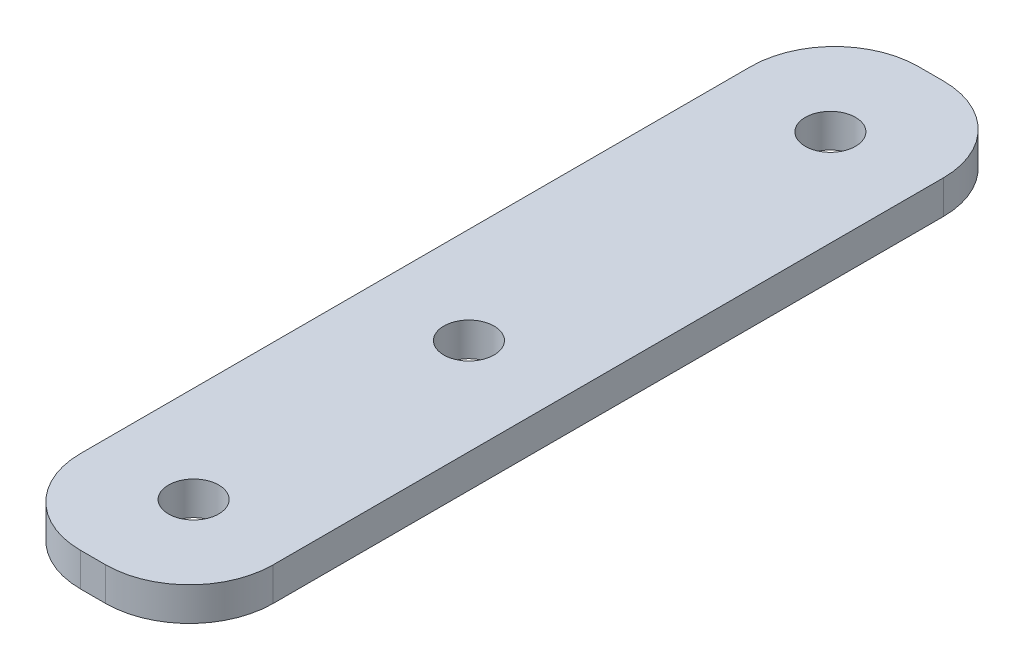
SolidWorks part; units mm, degrees
material "3.0205 (EN-AW 1200)"
ref_plane "Plan de face" through (0, 0, 0) normal (0, 0, 1) x (1, 0, 0)
ref_plane "Plan de dessus" through (0, 0, 0) normal (0, 1, 0) x (1, 0, 0)
ref_plane "Plan de droite" through (0, 0, 0) normal (1, 0, 0) x (0, 0, -1)
sketch "Esquisse1" plane through (0, 0, 0) normal (0, 0, 1) x (1, 0, 0)
  line L1 (0, 0) -> (11.5, 0)
  dimension "D2" = 11.5
extrude "Extru.-Mince1" add sketch "Esquisse1" along normal blind 50 thin thin type one direction reverse wall 2
sketch "Esquisse2" plane through (0, 2, 0) normal (0, 1, 0) x (1, 0, 0)
  line L0 (0, 0) -> (11.5, 0) construction
  line L1 (0, -50) -> (11.5, -50) construction
  line L2 (5.75, -6) -> (16.529, -16.4313) construction
  line L3 (16.529, -16.4313) -> (5.75, -27.5697) construction
  circle A0 centre (5.75, -6) radius 1.5
  circle A1 centre (5.75, -27.5697) radius 1.5
  circle A2 centre (5.75, -44) radius 1.5
  point P9 (5.75, 0)
  dimension "D1" = 6
  dimension "D2" = 3
  dimension "D3" = 6
  dimension "D6" = 21.5697
  dimension "D7" = 16.4303
  dimension "D4" = 15
  dimension "D5" = 15.5
extrude "Enlèv. mat.-Extru.1" cut sketch "Esquisse2" against normal blind 3
fillet "Congé1" radius 5 4 edges at (11.5, 1, 0) (0, 1, 50) (0, 1, 0) (11.5, 1, 50)
